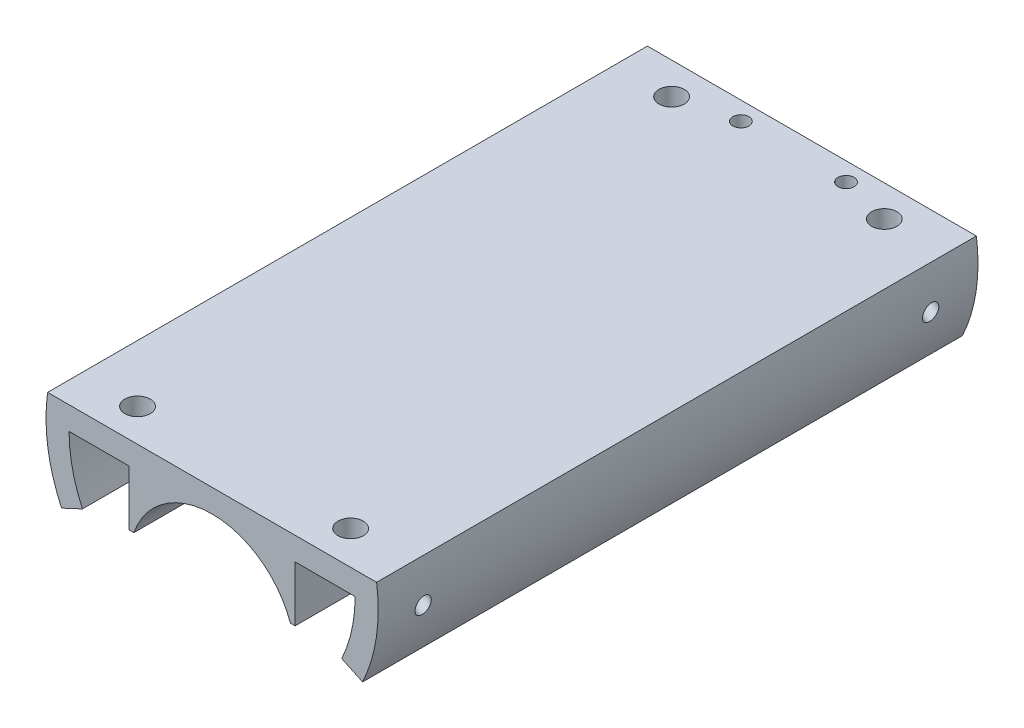
SolidWorks part; units mm, degrees
material "PET"
ref_plane "Front Plane" through (0, 0, 0) normal (0, 0, 1) x (1, 0, 0)
ref_plane "Top Plane" through (0, 0, 0) normal (0, 1, 0) x (1, 0, 0)
ref_plane "Right Plane" through (0, 0, 0) normal (1, 0, 0) x (0, 0, -1)
sketch "Sketch1" plane through (0, 0, 0) normal (0, 0, 1) x (1, 0, 0)
  line L0 (18, 0) -> (-18, 0)
  line L1 (18, 2.5) -> (-18, 2.5)
  line L2 (0, 0) -> (16.3135, -7.6071)
  line L3 (0, 0) -> (-16.3135, -7.6071)
  circle A0 centre (0, 0) radius 18
  circle A1 centre (0, 0) radius 15.5
  dimension "D1" = 36
  dimension "D4" = 25
  dimension "D5" = 25
  dimension "D2" = 2.5
  dimension "D3" = 2.5
extrude "Boss-Extrude1" add sketch "Sketch1" along normal blind 65 contours A1 L2 A0 L0 | A1 L0 A0 L1 | L0 A1 L1 | A1 L0 A0 L3 | A1 L1 A0 L0
sketch "Sketch2" plane through (0, 2.5, 0) normal (0, 1, 0) x (1, 0, 0)
  circle A0 centre (11.2395, -3.3946) radius 1.375
  circle A1 centre (-11.7605, -3.4431) radius 1.375
  circle A2 centre (11.3618, -61.3474) radius 1.375
  circle A3 centre (-11.638, -61.443) radius 1.375
  dimension "D1" = 2.75
  dimension "D2" = 2.75
  dimension "D3" = 2.75
  dimension "D4" = 2.75
extrude "Cut-Extrude1" cut sketch "Sketch2" against normal up to next
sketch "Sketch3" plane through (0, 0, 65) normal (0, 0, 1) x (1, 0, 0)
  line L0 (15.5, 0) -> (-15.5, 0) construction
  line L1 (-9, -6) -> (9, -6)
  line L2 (-9, -9) -> (9, -9)
  line L3 (-9, -9) -> (-9, 0)
  line L4 (-9, 0) -> (9, 0)
  line L5 (9, -9) -> (9, 0)
  circle A0 centre (0, -9) radius 9
  line M14 (-15.5, 0) -> (15.5, 0)
  dimension "D1" = 18
  dimension "D2" = 6
extrude "Boss-Extrude2" add sketch "Sketch3" against normal blind 65 contours A0 L3 L1 M14 | A0 L1 L5 L4
ref_plane "Plane1" through (-15.5885, -9, 0) normal (-0.866, -0.5, 0) x (0, 0, -1)
sketch "Sketch4" plane through (-15.5885, -9, 0) normal (-0.866, -0.5, 0) x (0, 0, -1)
  line L0 (-65, -11.0778) -> (0, -11.0778) construction
  line L1 (-65, -1.5688) -> (-65, -11.0778) construction
  circle A0 centre (-60, -7.0778) radius 0.875
  circle A1 centre (-5, -7.0778) radius 0.875
  dimension "D1" = 1.75
  dimension "D3" = 5
  dimension "D2" = 4
  dimension "D4" = 2
extrude "Cut-Extrude2" cut sketch "Sketch4" against normal up to surface (3.7953 mm away)
mirror "Mirror1" about plane through (0, 0, 0) normal (1, 0, 0) of "Cut-Extrude2"
sketch "Sketch5" plane through (0, 2.5, 0) normal (0, 1, 0) x (1, 0, 0)
  circle A0 centre (-5.7, -2) radius 0.875
  circle A1 centre (5.7, -2) radius 0.875
  dimension "D1" = 1.75
  dimension "D2" = 1.75
extrude "Cut-Extrude3" cut sketch "Sketch5" against normal up to next
